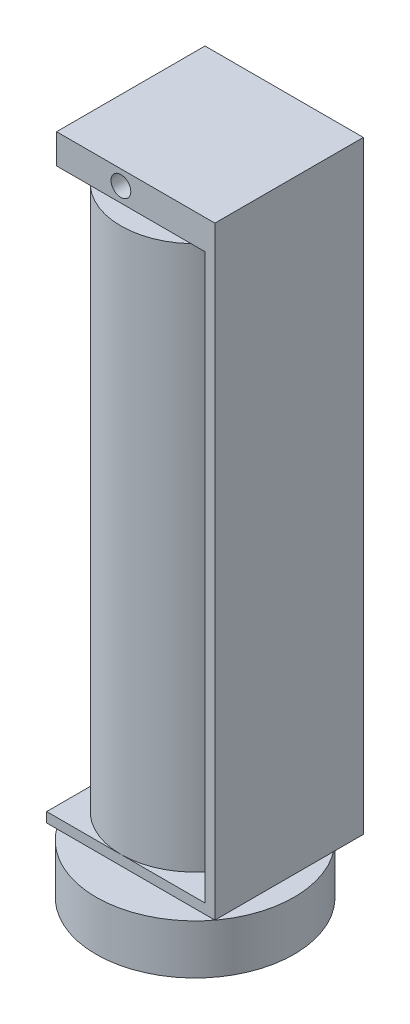
SolidWorks part; units mm, degrees
ref_plane "Front Plane" through (0, 0, 0) normal (0, 0, 1) x (1, 0, 0)
ref_plane "Top Plane" through (0, 0, 0) normal (0, 1, 0) x (1, 0, 0)
ref_plane "Right Plane" through (0, 0, 0) normal (1, 0, 0) x (0, 0, -1)
sketch "Sketch1" plane through (0, 0, 0) normal (0, 1, 0) x (1, 0, 0)
  circle A0 centre (0, 0) radius 20
extrude "Extrude1" add sketch "Sketch1" along normal blind 10
sketch "Sketch2" plane through (0, 10, 0) normal (0, 1, 0) x (1, 0, 0)
  circle A0 centre (0, 0) radius 2
extrude "Extrude2" add sketch "Sketch2" along normal blind 5
sketch "Sketch3" plane through (0, 15, 0) normal (0, 1, 0) x (1, 0, 0)
  circle A0 centre (0, 0) radius 15
extrude "Extrude3" add sketch "Sketch3" along normal blind 110
sketch "Sketch4" plane through (0, 15, 0) normal (0, -1, 0) x (1, 0, 0)
  line L1 (-15, 15) -> (19, 15)
  line L2 (-15, 15) -> (-15, -15)
  line L3 (-15, -15) -> (19, -15)
  line L4 (19, 15) -> (19, -15)
  dimension "D1" = 15
  dimension "D2" = 30
  dimension "D3" = 15
  dimension "D4" = 34
extrude "Extrude4" add sketch "Sketch4" along normal blind 2
sketch "Sketch5" plane through (0, 15, 0) normal (0, 1, 0) x (1, 0, 0)
  line L0 (0, 15) -> (19, 15) construction
  line L1 (17, 15) -> (19, 15)
  line L2 (17, 15) -> (17, -15)
  line L3 (17, -15) -> (19, -15)
  line L4 (19, 15) -> (19, -15)
  dimension "D1" = 2
extrude "Extrude5" add sketch "Sketch5" along normal blind 120
sketch "Sketch6" plane through (17, 0, 0) normal (-1, 0, 0) x (0, 0, 1)
  line L0 (15, 135) -> (15, 15) construction
  line L1 (-15, 135) -> (15, 135)
  line L2 (-15, 135) -> (-15, 129)
  line L3 (-15, 129) -> (15, 129)
  line L4 (15, 135) -> (15, 129)
  dimension "D1" = 6
extrude "Extrude6" add sketch "Sketch6" along normal blind 30
sketch "Sketch7" plane through (0, 0, 15) normal (0, 0, 1) x (1, 0, 0)
  line L0 (0, 125) -> (0, 15) construction
  line L1 (-13, 135) -> (19, 135) construction
  circle A0 centre (0.0001, 132) radius 2
  dimension "D2" = 4
  dimension "D1" = 0.0001
  dimension "D3" = 3
extrude "Cut-Extrude1" cut sketch "Sketch7" against normal blind 30
